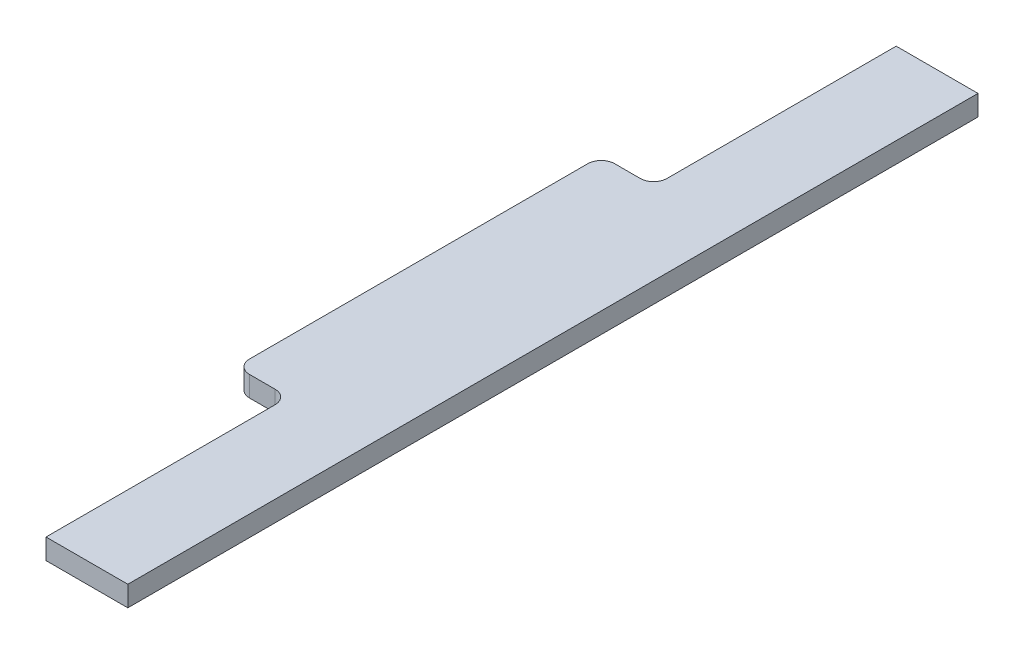
SolidWorks part; units mm, degrees
material "Low Carbon Steel"
ref_plane "Front Plane" through (0, 0, 0) normal (0, 0, 1) x (1, 0, 0)
ref_plane "Top Plane" through (0, 0, 0) normal (0, 1, 0) x (1, 0, 0)
ref_plane "Right Plane" through (0, 0, 0) normal (1, 0, 0) x (0, 0, -1)
sketch "Sketch1" plane through (0, 0, 0) normal (0, 1, 0) x (1, 0, 0)
  line L0 (0, 1156.75) -> (0, 1583.5)
  line L1 (0, 0) -> (152.4, 0)
  line L2 (0, 0) -> (0, 426.75)
  line L3 (0, 1583.5) -> (152.4, 1583.5)
  line L4 (152.4, 0) -> (152.4, 1583.5)
  line L5 (-25, 1131.75) -> (-72.6, 1131.75)
  line L6 (152.4, 791.75) -> (-97.6, 791.75) construction
  line L7 (-25, 451.75) -> (-72.6, 451.75)
  line L8 (-97.6, 1106.75) -> (-97.6, 476.75)
  arc A0 (-72.6, 1131.75) -> (-97.6, 1106.75) centre (-72.6, 1106.75) ccw
  arc A1 (-72.6, 451.75) -> (-97.6, 476.75) centre (-72.6, 476.75) cw
  arc A2 (0, 426.75) -> (-25, 451.75) centre (-25, 426.75) ccw
  arc A3 (-25, 1131.75) -> (0, 1156.75) centre (-25, 1156.75) ccw
  point P11 (-97.6, 1131.75)
  point P14 (-97.6, 451.75)
  point P19 (0, 1131.75)
  dimension "D6" = 25
  dimension "D1" = 1583.5
  dimension "D2" = 152.4
  dimension "D3" = 680
  dimension "D4" = 250
extrude "Boss-Extrude1" add sketch "Sketch1" along normal blind 38.1
other "Freeze***"
